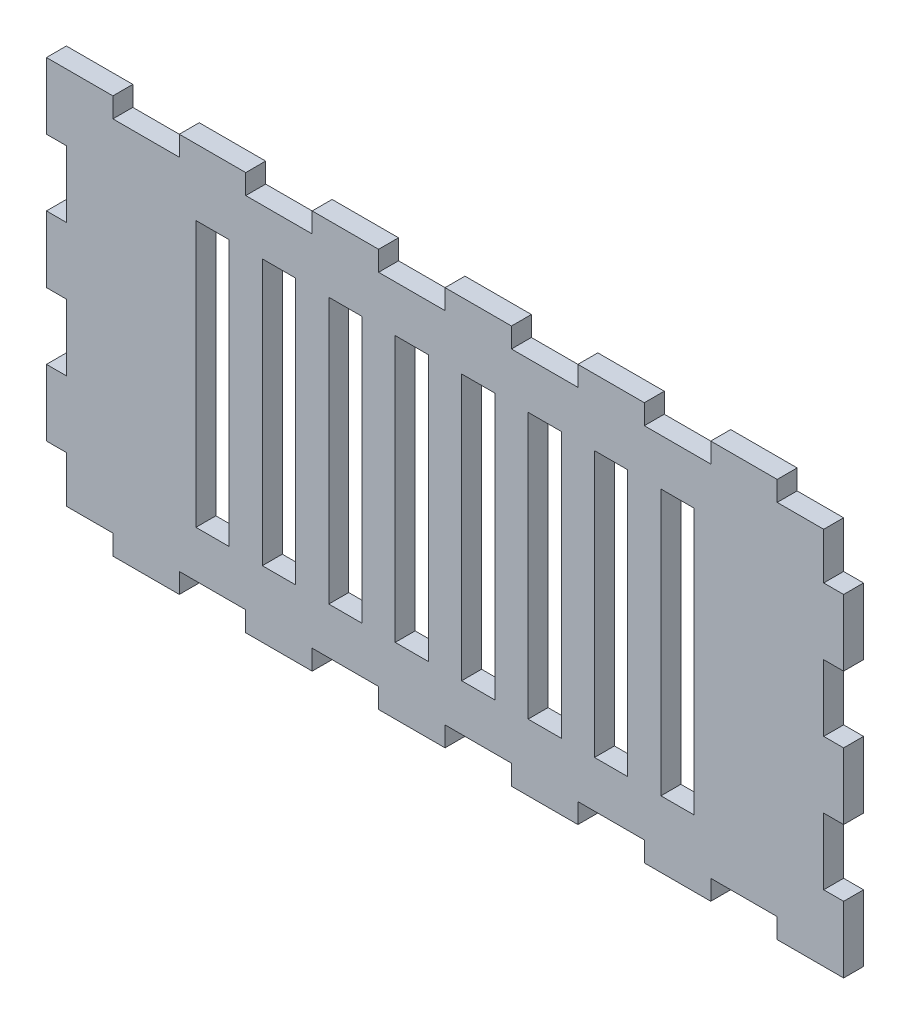
SolidWorks part; units mm, degrees
material "Beech"
ref_plane "Front Plane" through (0, 0, 0) normal (0, 0, 1) x (1, 0, 0)
ref_plane "Top Plane" through (0, 0, 0) normal (0, 1, 0) x (1, 0, 0)
ref_plane "Right Plane" through (0, 0, 0) normal (1, 0, 0) x (0, 0, -1)
sketch "Sketch1" plane through (0, 0, 0) normal (0, 0, 1) x (1, 0, 0)
  line L0 (120, 10) -> (117, 10)
  line L1 (0, 0) -> (120, 0)
  line L2 (0, 0) -> (0, 60)
  line L3 (0, 60) -> (120, 60)
  line L4 (120, 0) -> (120, 60)
  line L5 (117, 10) -> (117, 20)
  line L6 (117, 20) -> (120, 20)
  line L7 (117, 40) -> (120, 40)
  line L8 (117, 30) -> (117, 40)
  line L9 (120, 30) -> (117, 30)
  line L10 (117, 60) -> (120, 60)
  line L11 (117, 50) -> (117, 60)
  line L12 (120, 50) -> (117, 50)
  line L13 (3, 3) -> (10, 3)
  line L14 (10, 3) -> (10, 0)
  line L15 (20, 0) -> (20, 3)
  line L16 (20, 3) -> (30, 3)
  line L17 (30, 3) -> (30, 0)
  line L18 (40, 0) -> (40, 3)
  line L19 (40, 3) -> (50, 3)
  line L20 (50, 3) -> (50, 0)
  line L21 (60, 0) -> (60, 3)
  line L22 (60, 3) -> (70, 3)
  line L23 (70, 3) -> (70, 0)
  line L24 (80, 0) -> (80, 3)
  line L25 (80, 3) -> (90, 3)
  line L26 (90, 3) -> (90, 0)
  line L27 (100, 0) -> (100, 3)
  line L28 (100, 3) -> (110, 3)
  line L29 (110, 3) -> (110, 0)
  line L30 (110, 60) -> (110, 57)
  line L31 (110, 57) -> (117, 57)
  line L32 (100, 60) -> (100, 57)
  line L33 (100, 57) -> (90, 57)
  line L34 (0, 50) -> (3, 50)
  line L35 (3, 50) -> (3, 40)
  line L36 (3, 40) -> (0, 40)
  line L37 (3, 20) -> (0, 20)
  line L38 (3, 30) -> (3, 20)
  line L39 (0, 30) -> (3, 30)
  line L40 (3, 0) -> (0, 0)
  line L41 (3, 10) -> (3, 0)
  line L42 (0, 10) -> (3, 10)
  line L43 (90, 57) -> (90, 60)
  line L44 (80, 60) -> (80, 57)
  line L45 (80, 57) -> (70, 57)
  line L46 (70, 57) -> (70, 60)
  line L47 (60, 60) -> (60, 57)
  line L48 (60, 57) -> (50, 57)
  line L49 (50, 57) -> (50, 60)
  line L50 (40, 60) -> (40, 57)
  line L51 (40, 57) -> (30, 57)
  line L52 (30, 57) -> (30, 60)
  line L53 (20, 60) -> (20, 57)
  line L54 (20, 57) -> (10, 57)
  line L55 (10, 57) -> (10, 60)
  point P45 (110, 58.5)
  dimension "D1" = 120
  dimension "D2" = 60
  dimension "D3" = 5
  dimension "D4" = 10
  dimension "D5" = 10
  dimension "D7" = 10
  dimension "D8" = 3
  dimension "D9" = 10
  dimension "D11" = 10
  dimension "D12" = 10
  dimension "D13" = 3
  dimension "D10" = 10
  dimension "D15" = 3
  dimension "D16" = 3
  dimension "D17" = 10
  dimension "D18" = 10
  dimension "D19" = 10
  dimension "D20" = 3
  dimension "D22" = 5
  dimension "D14" = 3
  dimension "D6" = 3
extrude "Boss-Extrude1" add sketch "Sketch1" along normal blind 3
sketch "Sketch2" plane through (0, 0, 3) normal (0, 0, 1) x (1, 0, 0)
  line L0 (0, 60) -> (10, 60) construction
  line L1 (22.5, 50) -> (27.5, 50)
  line L2 (22.5, 50) -> (22.5, 10)
  line L3 (22.5, 10) -> (27.5, 10)
  line L4 (27.5, 50) -> (27.5, 10)
  line L6 (0, 30) -> (0, 40) construction
  line L7 (32.5, 50) -> (37.5, 50)
  line L8 (37.5, 50) -> (37.5, 10)
  line L9 (32.5, 50) -> (32.5, 10)
  line L10 (32.5, 10) -> (37.5, 10)
  line L11 (42.5, 50) -> (47.5, 50)
  line L12 (47.5, 50) -> (47.5, 10)
  line L13 (42.5, 50) -> (42.5, 10)
  line L14 (42.5, 10) -> (47.5, 10)
  line L15 (52.5, 50) -> (57.5, 50)
  line L16 (57.5, 50) -> (57.5, 10)
  line L17 (52.5, 50) -> (52.5, 10)
  line L18 (52.5, 10) -> (57.5, 10)
  line L19 (62.5, 50) -> (67.5, 50)
  line L20 (67.5, 50) -> (67.5, 10)
  line L21 (62.5, 50) -> (62.5, 10)
  line L22 (62.5, 10) -> (67.5, 10)
  line L23 (72.5, 50) -> (77.5, 50)
  line L24 (77.5, 50) -> (77.5, 10)
  line L25 (72.5, 50) -> (72.5, 10)
  line L26 (72.5, 10) -> (77.5, 10)
  line L27 (82.5, 50) -> (87.5, 50)
  line L28 (87.5, 50) -> (87.5, 10)
  line L29 (82.5, 50) -> (82.5, 10)
  line L30 (82.5, 10) -> (87.5, 10)
  line L31 (92.5, 50) -> (97.5, 50)
  line L32 (97.5, 50) -> (97.5, 10)
  line L33 (92.5, 50) -> (92.5, 10)
  line L34 (92.5, 10) -> (97.5, 10)
  dimension "D1" = 40
  dimension "D2" = 5
  dimension "D3" = 10
  dimension "D4" = 22.5
extrude "Cut-Extrude1" cut sketch "Sketch2" against normal blind 10
